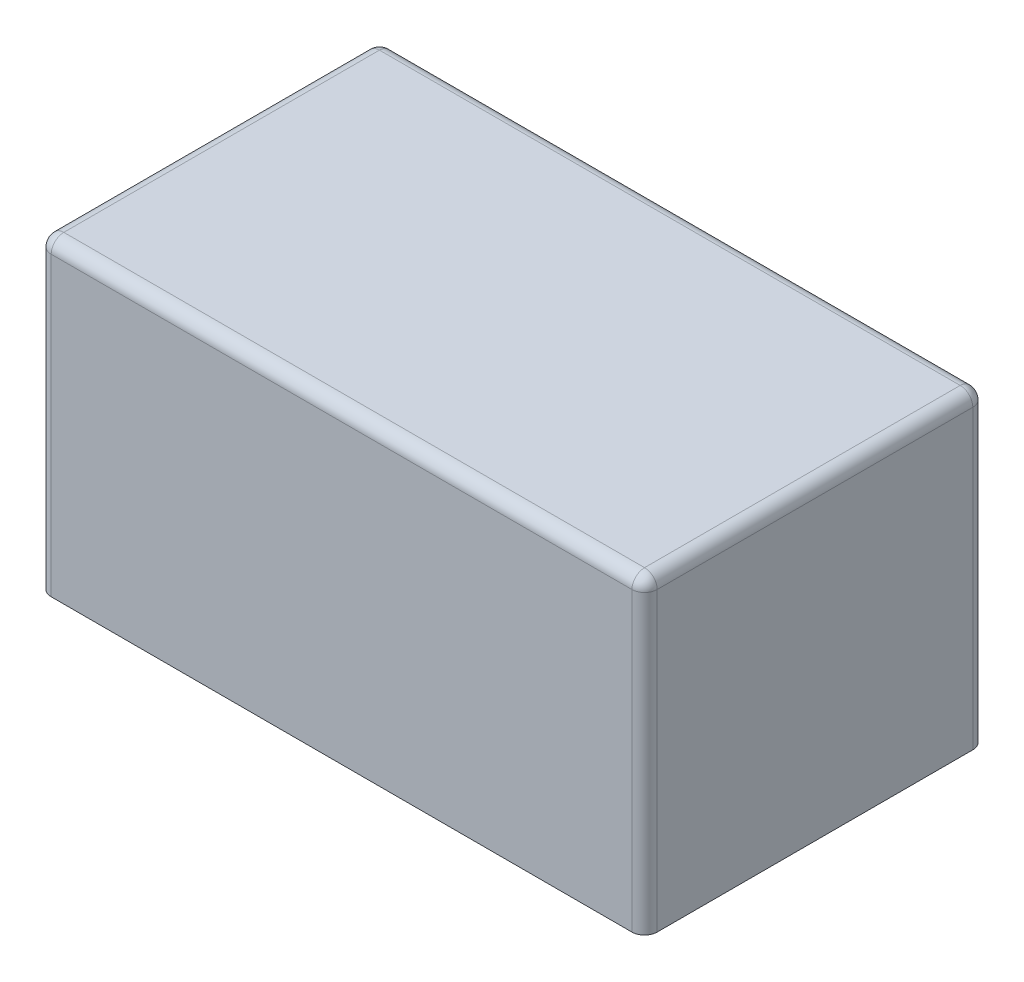
SolidWorks part; units mm, degrees
ref_plane "正面" through (0, 0, 0) normal (0, 0, 1) x (1, 0, 0)
ref_plane "平面" through (0, 0, 0) normal (0, 1, 0) x (1, 0, 0)
ref_plane "右側面" through (0, 0, 0) normal (1, 0, 0) x (0, 0, -1)
sketch "ｽｹｯﾁ1" plane through (0, 0, 0) normal (0, 1, 0) x (1, 0, 0)
  line L0 (-27.852, 20.1507) -> (20.148, 20.1507)
  line L1 (-27.852, 20.1507) -> (-27.852, -6.8493)
  line L2 (20.148, 20.1507) -> (20.148, -6.8493)
  line L3 (-27.852, -6.8493) -> (20.148, -6.8493)
  dimension "D1" = 27
  dimension "D2" = 48
extrude "ﾎﾞｽ - 押し出し1" add sketch "ｽｹｯﾁ1" along normal blind 24.5
fillet "ﾌｨﾚｯﾄ1" radius 1 8 edges at (-27.852, 24.5, -6.6507) (-3.852, 24.5, 6.8493) (20.148, 24.5, -6.6507) (-3.852, 24.5, -20.1507) (-27.852, 12.25, -20.1507) (20.148, 12.25, -20.1507) (20.148, 12.25, 6.8493) (-27.852, 12.25, 6.8493)
sketch "ｽｹｯﾁ4" plane through (0, 0, 0) normal (0, -1, 0) x (1, 0, 0)
  line L0 (-26.852, 5.8493) -> (19.148, 5.8493)
  line L1 (-26.852, 5.8493) -> (-26.852, -19.1507)
  line L2 (19.148, 5.8493) -> (19.148, -19.1507)
  line L3 (-26.852, -19.1507) -> (19.148, -19.1507)
  dimension "D1" = 46
  dimension "D2" = 25
extrude "ｶｯﾄ - 押し出し1" cut sketch "ｽｹｯﾁ4" against normal blind 23.5 contours L0 L2 L3 L1
